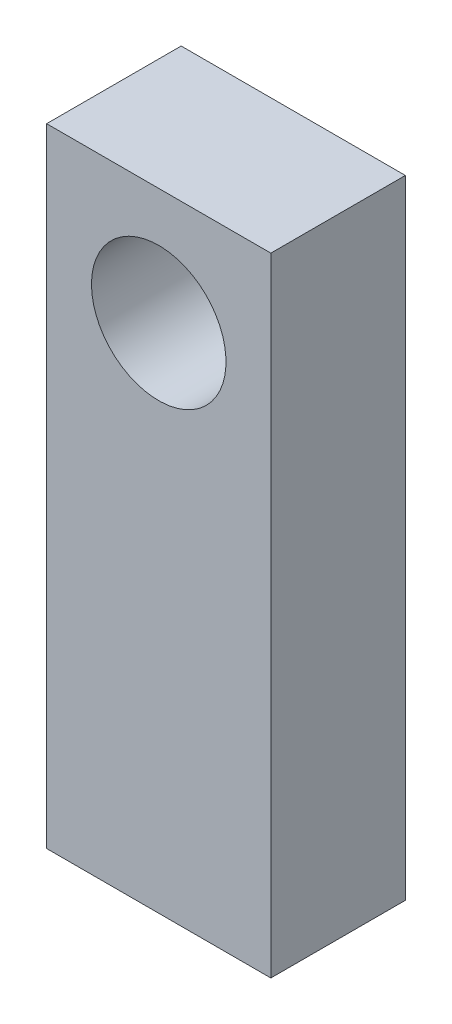
SolidWorks part; units mm, degrees
material "Oak"
ref_plane "Front Plane" through (0, 0, 0) normal (0, 0, 1) x (1, 0, 0)
ref_plane "Top Plane" through (0, 0, 0) normal (0, 1, 0) x (1, 0, 0)
ref_plane "Right Plane" through (0, 0, 0) normal (1, 0, 0) x (0, 0, -1)
sketch "Sketch1" plane through (0, 0, 0) normal (0, 0, 1) x (1, 0, 0)
  line L0 (0, 0) -> (0, -28.956) construction
  line L9 (-6.35, -28.956) -> (6.35, -28.956)
  line L10 (-6.35, -28.956) -> (-6.35, 6.604)
  line L11 (-6.35, 6.604) -> (6.35, 6.604)
  line L12 (6.35, 6.604) -> (6.35, -28.956)
  circle A0 centre (0, 0) radius 3.81
  point P7 (0, -28.956)
  point P9 (6.35, 6.6706)
  dimension "D1" = 7.62
  dimension "D2" = 28.956
  dimension "D3" = 12.7
  dimension "D4" = 35.56
extrude "Boss-Extrude1" add sketch "Sketch1" along normal blind 7.62
